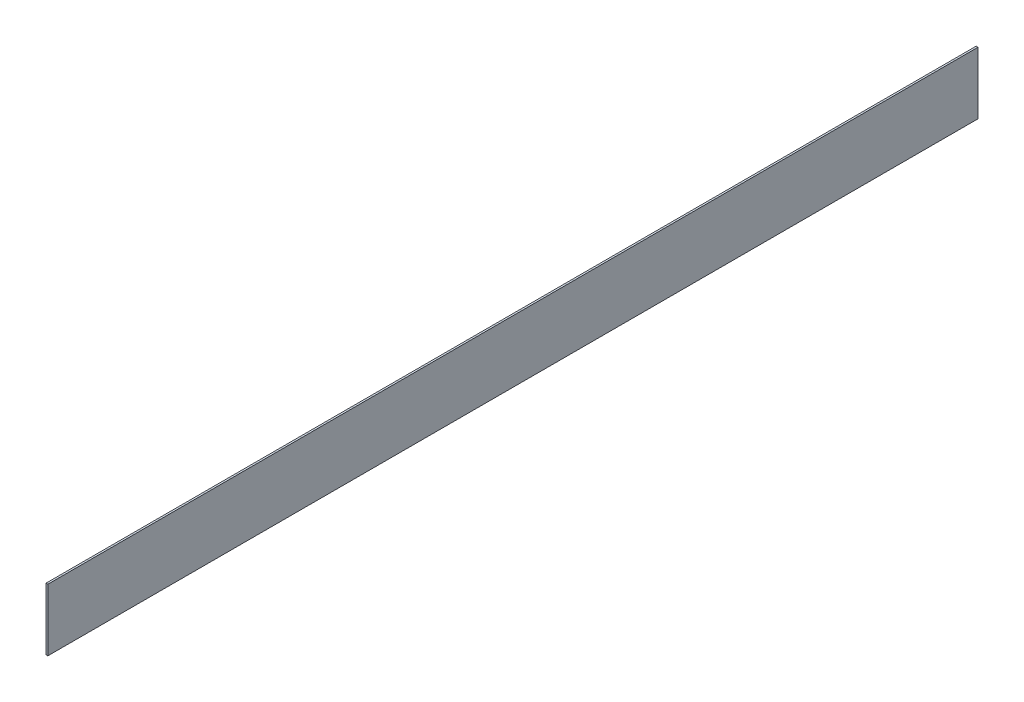
SolidWorks part; units mm, degrees
material "冷板"
ref_plane "前视基准面" through (0, 0, 0) normal (0, 0, 1) x (1, 0, 0)
ref_plane "上视基准面" through (0, 0, 0) normal (0, 1, 0) x (1, 0, 0)
ref_plane "右视基准面" through (0, 0, 0) normal (1, 0, 0) x (0, 0, -1)
sketch "草图1" plane through (0, 0, 0) normal (0, 0, 1) x (1, 0, 0)
  line L1 (-6, 200) -> (6, 200)
  line L2 (-6, 200) -> (-6, -200)
  line L3 (-6, -200) -> (6, -200)
  line L4 (6, 200) -> (6, -200)
  line L5 (-6, 200) -> (6, -200) construction
  line L6 (-6, -200) -> (6, 200) construction
  point P0 (0, 0)
  dimension "D1" = 12
  dimension "D2" = 400
extrude "凸台-拉伸1" add sketch "草图1" along normal mid plane 6000
equation "\"零件重量\"= \"SW-质量\""
